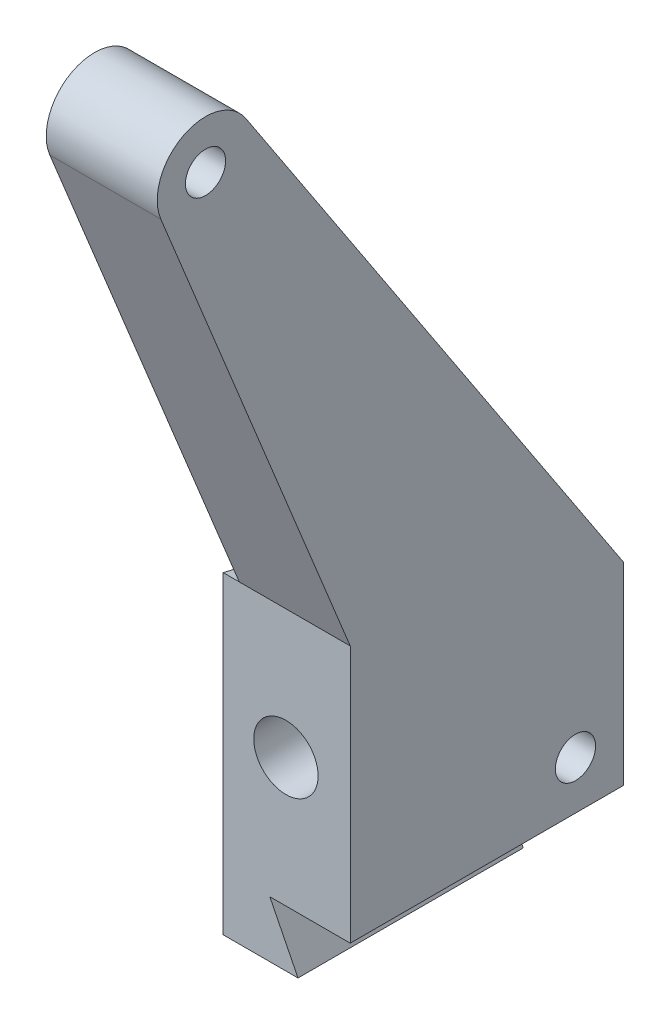
SolidWorks part; units mm, degrees
ref_plane "Front Plane" through (0, 0, 0) normal (0, 0, 1) x (1, 0, 0)
ref_plane "Top Plane" through (0, 0, 0) normal (0, 1, 0) x (1, 0, 0)
ref_plane "Right Plane" through (0, 0, 0) normal (1, 0, 0) x (0, 0, -1)
sketch "Sketch1" plane through (0, 0, 0) normal (1, 0, 0) x (0, 0, -1)
  line L0 (0, 0) -> (0, 16)
  line L1 (0, 16) -> (-23.4951, 51.6508)
  line L2 (-17, 20) -> (-17, 0)
  line L3 (-17, 0) -> (0, 0)
  line L4 (-17, 20) -> (-28.7777, 48.8667)
  arc A0 (-23.4951, 51.6508) -> (-28.7777, 48.8667) centre (-26, 50) ccw
  circle A1 centre (-26, 50) radius 1.25
  dimension "D4" = 6
  dimension "D5" = 9
  dimension "D6" = 50
  dimension "D7" = 2.5
  dimension "D1" = 20
  dimension "D2" = 16
  dimension "D3" = 17
extrude "Boss-Extrude1" add sketch "Sketch1" along normal blind 7.9
sketch "Sketch2" plane through (7.9, 0, 0) normal (1, 0, 0) x (0, 0, -1)
  line L0 (-17, 20) -> (-17, 0) construction
  line L1 (-17, 5) -> (0, 5)
  line L2 (-17, 5) -> (-17, 0)
  line L3 (-17, 0) -> (0, 0)
  line L4 (0, 5) -> (0, 0)
  line L5 (0, 0) -> (0, 16) construction
  dimension "D1" = 5
extrude "Cut-Extrude1" [suppressed] cut sketch "Sketch2" against normal blind 4
sketch "Sketch3" plane through (0, 0, 0) normal (0, 0, -1) x (-1, 0, 0)
  line L0 (-7.9, 0) -> (-4.9, 0)
  line L1 (-7.9, 0) -> (0, 0) construction
  line L2 (-4.9, 0) -> (-2.9, 4)
  line L3 (-2.9, 4) -> (-7.9, 4)
  line L4 (-7.9, 0) -> (-7.9, 16) construction
  line L5 (-7.9, 4) -> (-7.9, 0)
  dimension "D1" = 5
  dimension "D2" = 3
  dimension "D3" = 4
extrude "Cut-Extrude2" cut sketch "Sketch3" against normal through all
sketch "Sketch5" plane through (7.9, 0, 0) normal (1, 0, 0) x (0, 0, -1)
  line L0 (0, 4) -> (0, 16) construction
  line L1 (-17, 4) -> (0, 4) construction
  circle A0 centre (-3, 7) radius 1
  dimension "D1" = 2
  dimension "D3" = 3
  dimension "D2" = 3
hole_wizard "M3x0.5 Tapped Hole1" positions "3DSketch1" profile "Sketch6" tap size "M3x0.5" standard "ANSI Metric" end condition through all
sketch3d "3DSketch1"
  point P0 (7.9, 7, 3)
sketch "Sketch6" plane through (7.9, 7, 3) normal (0, 1, 0) x (0, 0, -1)
  line L0 (0, 0) -> (0, 7.9)
  line L1 (0, 7.9) -> (1.25, 7.9)
  line L2 (1.25, 7.9) -> (1.25, 0)
  line L5 (1.25, 0) -> (0, 0)
  line L11 (0, -6.35) -> (0, 107.95) construction
  dimension "Thread Major Dia." = 2.5
  dimension "Thru Tap Drill Depth" = 7.9
sketch "Sketch7" plane through (0, 0, 0) normal (0, 0, -1) x (-1, 0, 0)
  line L1 (0, 0) -> (-8, 0)
  line L2 (0, 0) -> (0, 0.5)
  line L3 (0, 0.5) -> (-8, 0.5)
  line L4 (-8, 0) -> (-8, 0.5)
  dimension "D1" = 0.5
  dimension "D2" = 8
extrude "Cut-Extrude3" cut sketch "Sketch7" against normal through all
sketch "Sketch8" plane through (0, 0, 17) normal (0, 0, 1) x (1, 0, 0)
  line L0 (2.9, 4) -> (7.9, 4) construction
  line L1 (7.9, 20) -> (7.9, 4) construction
  circle A0 centre (3.9, 12) radius 2
  point P4 (5.4, 4)
  dimension "D1" = 4
  dimension "D2" = 8
  dimension "D3" = 4
extrude "Cut-Extrude4" cut sketch "Sketch8" against normal through all
sketch "Sketch9" plane through (0, 0, 0) normal (0, 0, -1) x (-1, 0, 0)
  line L0 (-4.65, 0.5) -> (-2.9, 4)
  line L1 (-2.9, 4) -> (0, 4)
  line L2 (0, 0.5) -> (0, 16) construction
  line L3 (0, 4) -> (0, 0.5)
  line L4 (0, 0.5) -> (-4.65, 0.5)
extrude "Cut-Extrude5" cut sketch "Sketch9" against normal blind 3
sketch "Sketch11" plane through (0, 0, 0) normal (-1, 0, 0) x (0, 0, 1)
  line L0 (0, 16) -> (17, 20)
  line L1 (17, 20) -> (28.7777, 48.8667)
  line L2 (23.4951, 51.6508) -> (0, 16)
  arc A0 (28.7777, 48.8667) -> (23.4951, 51.6508) centre (26, 50) ccw
extrude "Cut-Extrude6" cut sketch "Sketch11" against normal blind 1
